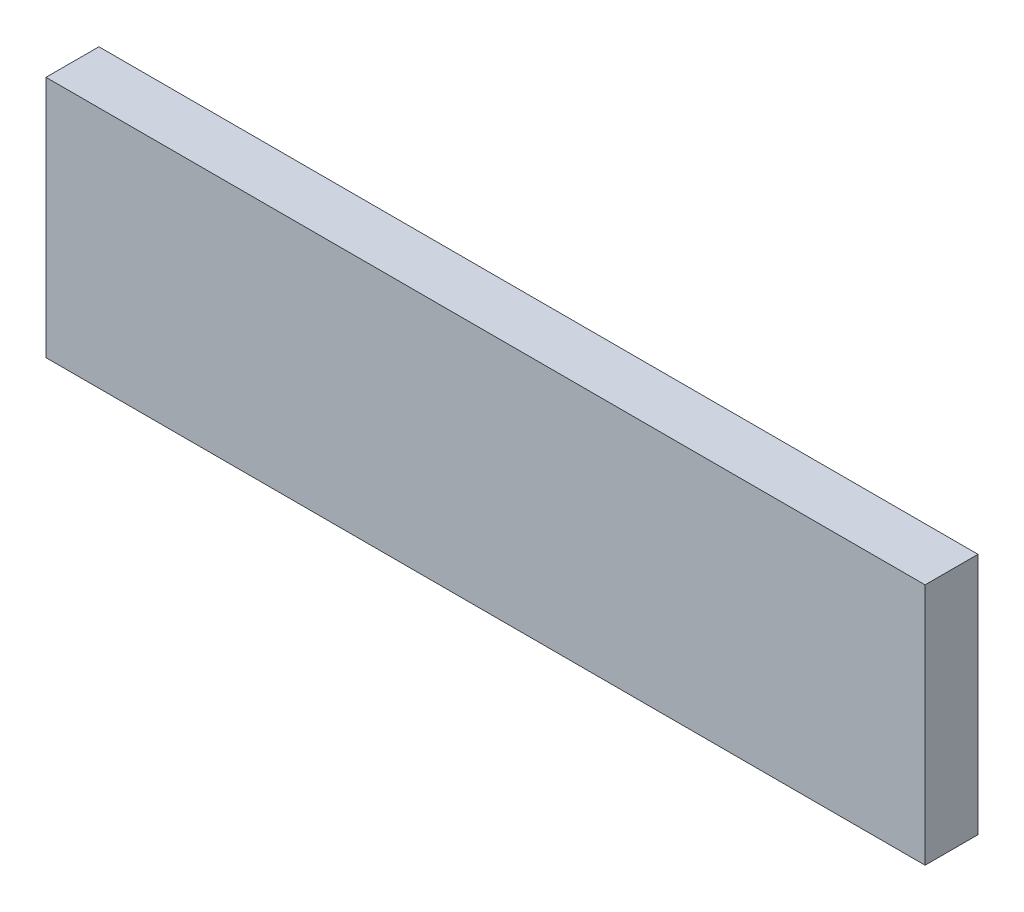
SolidWorks part; units mm, degrees
ref_plane "Front Plane" through (0, 0, 0) normal (0, 0, 1) x (1, 0, 0)
ref_plane "Top Plane" through (0, 0, 0) normal (0, 1, 0) x (1, 0, 0)
ref_plane "Right Plane" through (0, 0, 0) normal (1, 0, 0) x (0, 0, -1)
other "Configuration Table"
sketch "Sketch1" plane through (0, 0, 0) normal (0, 0, 1) x (1, 0, 0)
  line L1 (702, 1469) -> (1350, 1469)
  line L2 (702, 1469) -> (702, 1648)
  line L3 (702, 1648) -> (1350, 1648)
  line L4 (1350, 1469) -> (1350, 1648)
extrude "DET2_PU_dilimi_arka_1" add sketch "Sketch1" against normal blind 39 from offset 758.5 separate body
